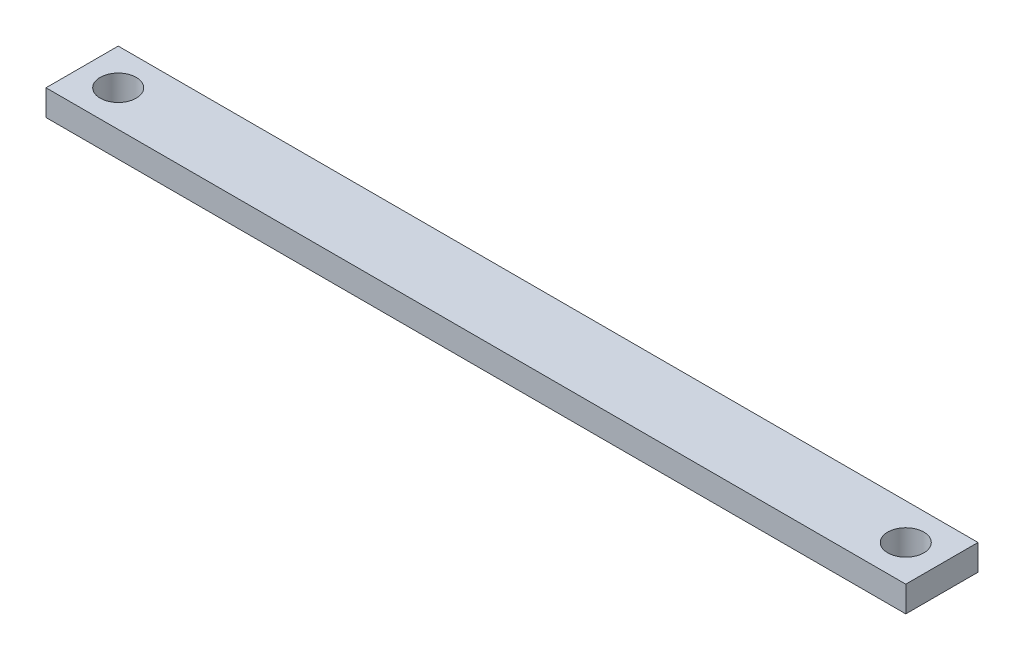
SolidWorks part; units mm, degrees
ref_plane "Plan de face" through (0, 0, 0) normal (0, 0, 1) x (1, 0, 0)
ref_plane "Plan de dessus" through (0, 0, 0) normal (0, 1, 0) x (1, 0, 0)
ref_plane "Plan de droite" through (0, 0, 0) normal (1, 0, 0) x (0, 0, -1)
sketch "Esquisse1" plane through (0, 0, 0) normal (0, 1, 0) x (1, 0, 0)
  line L1 (-260, -21) -> (260, -21)
  line L2 (-260, -21) -> (-260, 21)
  line L3 (-260, 21) -> (260, 21)
  line L4 (260, -21) -> (260, 21)
  line L5 (-260, -21) -> (260, 21) construction
  line L6 (-260, 21) -> (260, -21) construction
  point P0 (0, 0)
  dimension "D1" = 520
  dimension "D2" = 42
extrude "Boss.-Extru.1" add sketch "Esquisse1" along normal blind 15
sketch "Esquisse2" plane through (0, 15, 0) normal (0, 1, 0) x (1, 0, 0)
  line L0 (-260, 21) -> (-198, -21) construction
  line L1 (-260, -21) -> (260, -21) construction
  line L2 (-198, -21) -> (-198, 21) construction
  line L3 (260, 21) -> (-260, 21) construction
  line L4 (-198, 21) -> (-260, 21) construction
  line L5 (260, 21) -> (198, -21) construction
  line L6 (198, -21) -> (260, -21) construction
  line L7 (260, -21) -> (260, 21) construction
  circle A0 centre (-229, 0) radius 10.5
  circle A1 centre (229, 0) radius 10.5
  dimension "D1" = 21
  dimension "D2" = 21
extrude "Enlèv. mat.-Extru.1" cut sketch "Esquisse2" against normal blind 15
sketch "Esquisse3" plane through (0, 15, 0) normal (0, 1, 0) x (1, 0, 0)
  line L0 (260, 21) -> (-260, 21) construction
  line L1 (-260, -21) -> (-250, -21)
  line L2 (-260, -21) -> (-260, 21)
  line L3 (-260, 21) -> (-250, 21)
  line L4 (-250, -21) -> (-250, 21)
  line L6 (260, -21) -> (250, -21)
  line L7 (260, -21) -> (260, 21)
  line L8 (260, 21) -> (250, 21)
  line L9 (250, -21) -> (250, 21)
  dimension "D1" = 10
  dimension "D2" = 10
extrude "Enlèv. mat.-Extru.2" cut sketch "Esquisse3" against normal through all
